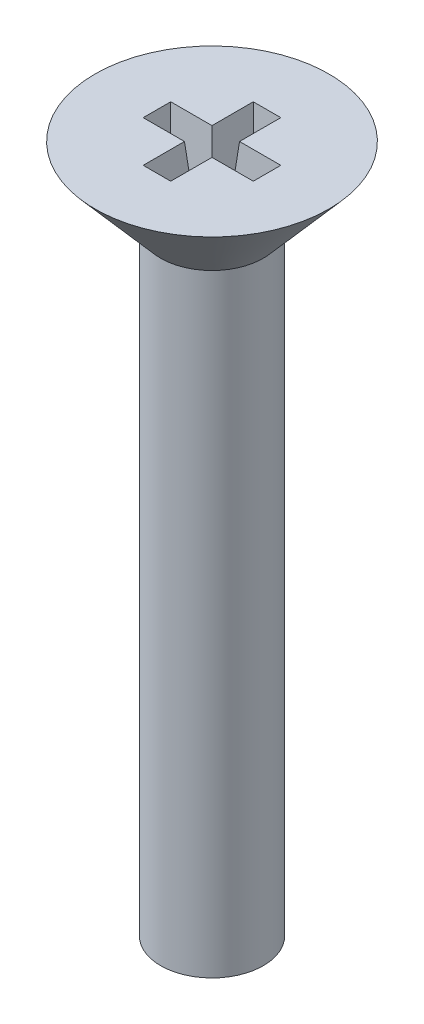
SolidWorks part; units mm, degrees
ref_plane "Front Plane" through (0, 0, 0) normal (0, 0, 1) x (1, 0, 0)
ref_plane "Top Plane" through (0, 0, 0) normal (0, 1, 0) x (1, 0, 0)
ref_plane "Right Plane" through (0, 0, 0) normal (1, 0, 0) x (0, 0, -1)
sketch "Sketch1" plane through (0, 0, 0) normal (0, 0, 1) x (1, 0, 0)
  line L1 (1.4224, 0) -> (3.2385, 2.0892)
  line L5 (3.2385, 2.0892) -> (0, 2.0892)
  line L6 (0, 2.0892) -> (0, 0)
  line L7 (0, 0) -> (0, -16.9608)
  line L8 (0, -16.9608) -> (1.4224, -16.9608)
  line L9 (1.4224, -16.9608) -> (1.4224, 0)
  line L11 (1.4224, 0) -> (0, 0) construction
  dimension "D1" = 19.05
  dimension "D2" = 1.4224
  dimension "D3" = 41
  dimension "D4" = 3.2385
revolve "Revolve1" add sketch "Sketch1" angle 360 about L7
sketch "Sketch2" plane through (0, 2.0892, 0) normal (0, 1, 0) x (1, 0, 0)
  line L0 (-0.381, 1.524) -> (0.381, 1.524)
  line L1 (0.381, 1.524) -> (0.381, 0.381)
  line L2 (0.381, 0.381) -> (1.524, 0.381)
  line L3 (1.524, 0.381) -> (1.524, -0.381)
  line L4 (1.524, -0.381) -> (0.381, -0.381)
  line L5 (0.381, -0.381) -> (0.381, -1.524)
  line L6 (0.381, -1.524) -> (-0.381, -1.524)
  line L7 (-0.381, -1.524) -> (-0.381, -0.381)
  line L8 (-0.381, -0.381) -> (-1.524, -0.381)
  line L9 (-1.524, -0.381) -> (-1.524, 0.381)
  line L10 (-1.524, 0.381) -> (-0.381, 0.381)
  line L11 (-0.381, 0.381) -> (-0.381, 1.524)
  line L12 (0, 1.524) -> (0, 0) construction
  line L13 (0, 0) -> (1.524, 0) construction
  line L15 (0, -1.524) -> (0, 0) construction
  line L16 (-1.524, 0) -> (0, 0) construction
  point P18 (0.3715, 0.3715)
  dimension "D1" = 0.762
  dimension "D2" = 1.524
extrude "Cut-Extrude1" cut sketch "Sketch2" against normal blind 2.159 draft 5
